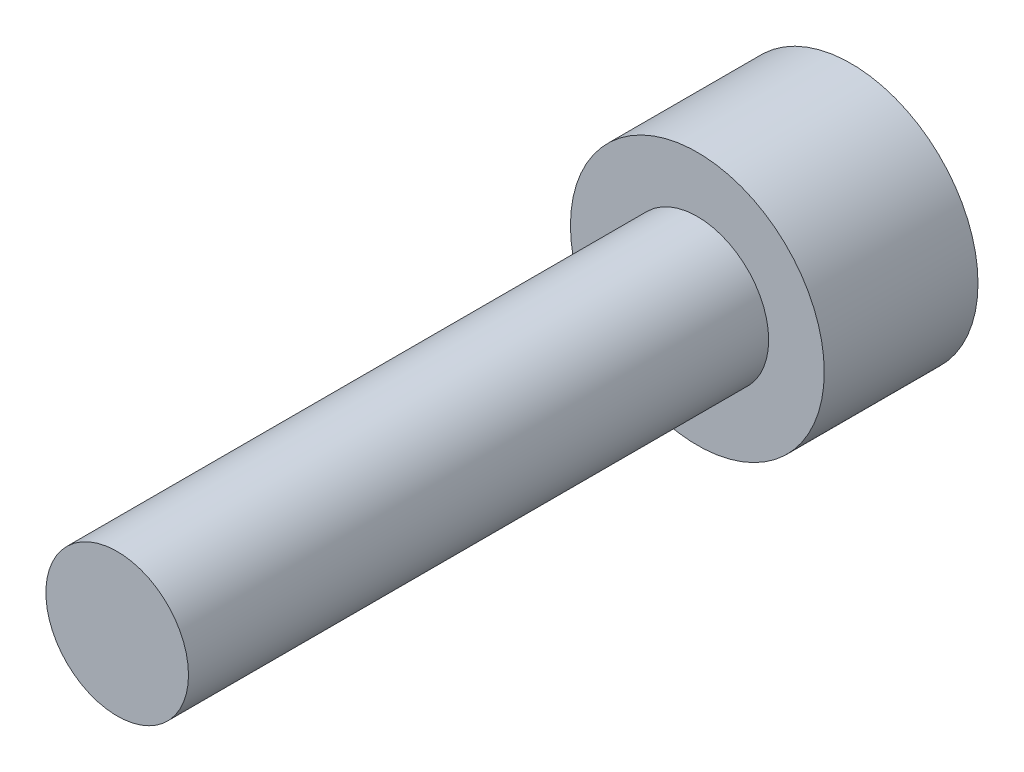
SolidWorks part; units mm, degrees
ref_plane "Front Plane" through (0, 0, 0) normal (0, 0, 1) x (1, 0, 0)
ref_plane "Top Plane" through (0, 0, 0) normal (0, 1, 0) x (1, 0, 0)
ref_plane "Right Plane" through (0, 0, 0) normal (1, 0, 0) x (0, 0, -1)
sketch "Sketch1" plane through (0, 0, 0) normal (0, 0, 1) x (1, 0, 0)
  circle A0 centre (0, 0) radius 2.625
  dimension "D1" = 5.25
extrude "Boss-Extrude1" add sketch "Sketch1" along normal blind 3.18 contours A0
sketch "Sketch2" plane through (0, 0, 3.18) normal (0, 0, 1) x (1, 0, 0)
  circle A0 centre (0, 0) radius 1.475
  dimension "D1" = 2.95
extrude "Boss-Extrude2" add sketch "Sketch2" along normal blind 12
